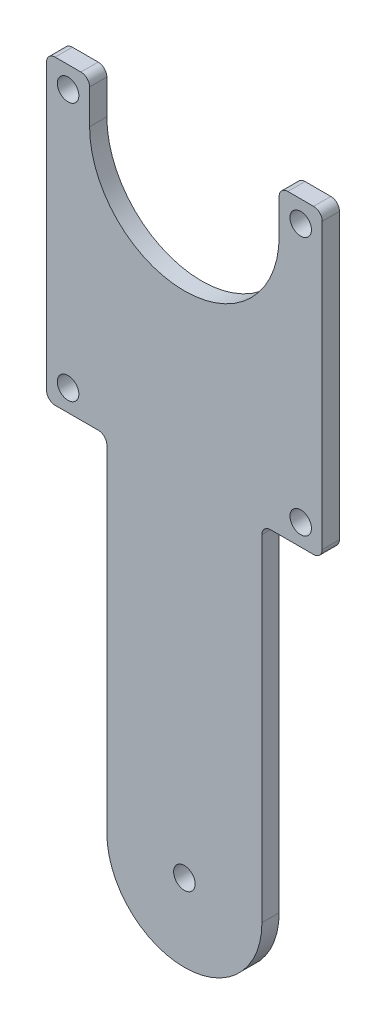
SolidWorks part; units mm, degrees
material "自訂玻璃纖維"
ref_plane "前基準面" through (0, 0, 0) normal (0, 0, 1) x (1, 0, 0)
ref_plane "上基準面" through (0, 0, 0) normal (0, 1, 0) x (1, 0, 0)
ref_plane "右基準面" through (0, 0, 0) normal (1, 0, 0) x (0, 0, -1)
sketch "草圖1" plane through (0, 0, 0) normal (0, 0, 1) x (1, 0, 0)
  line L0 (-6.9514, 19.5958) -> (-3.9514, 19.5958)
  line L1 (-7.9514, 18.5958) -> (-7.9514, -10.4042)
  line L2 (24.0486, -10.4042) -> (24.0486, 18.5958)
  line L3 (24.0486, -10.4042) -> (24.0486, -14.4042)
  line L4 (20.0486, 19.5958) -> (23.0486, 19.5958)
  line L5 (19.0486, 15.5958) -> (19.0486, 14.5958)
  line L6 (-2.9514, 18.5958) -> (-2.9514, 15.5958)
  line L7 (23.0486, -15.4042) -> (18.0486, -15.4042)
  line L8 (19.0486, 18.5958) -> (19.0486, 15.5958)
  line L9 (17.0486, -16.4042) -> (17.0486, -55.4042)
  line L10 (-7.9514, -10.4042) -> (-7.9514, -14.4042)
  line L11 (-6.9514, -15.4042) -> (-1.9514, -15.4042)
  line L12 (-0.9514, -16.4042) -> (-0.9514, -55.4042)
  line L13 (-2.9514, 14.5958) -> (-2.9514, 15.5958)
  circle A0 centre (-5.4514, -12.9042) radius 1.25
  circle A1 centre (21.5486, -12.9042) radius 1.25
  circle A2 centre (-5.4514, 17.0958) radius 1.25
  circle A3 centre (21.5486, 17.0958) radius 1.25
  arc A4 (19.0486, 14.5958) -> (-2.9514, 14.5958) centre (8.0486, 14.5958) cw
  arc A5 (23.0486, 19.5958) -> (24.0486, 18.5958) centre (23.0486, 18.5958) cw
  arc A6 (20.0486, 19.5958) -> (19.0486, 18.5958) centre (20.0486, 18.5958) ccw
  arc A7 (-0.9514, -55.4042) -> (17.0486, -55.4042) centre (8.0486, -55.4042) ccw
  arc A8 (-3.9514, 19.5958) -> (-2.9514, 18.5958) centre (-3.9514, 18.5958) cw
  arc A9 (-6.9514, 19.5958) -> (-7.9514, 18.5958) centre (-6.9514, 18.5958) ccw
  arc A10 (-7.9514, -14.4042) -> (-6.9514, -15.4042) centre (-6.9514, -14.4042) ccw
  circle A11 centre (8.0486, -55.4042) radius 1.25
  arc A12 (-1.9514, -15.4042) -> (-0.9514, -16.4042) centre (-1.9514, -16.4042) cw
  arc A13 (18.0486, -15.4042) -> (17.0486, -16.4042) centre (18.0486, -16.4042) ccw
  arc A14 (24.0486, -14.4042) -> (23.0486, -15.4042) centre (23.0486, -14.4042) cw
  point P20 (24.0486, 19.5958)
  point P25 (-2.9514, 14.5958)
  point P28 (-2.9514, 19.5958)
  point P31 (8.0486, -55.4042)
  point P47 (-1.2443, -15.6971)
  dimension "D3" = 2.5
  dimension "D4" = 27
  dimension "D5" = 27
  dimension "D7" = 39
  dimension "D10" = 2.5
  dimension "D13" = 9
  dimension "D11" = 2.5
  dimension "D16" = 1
  dimension "D1" = 2.5
  dimension "D2" = 5
  dimension "D6" = 30
  dimension "D8" = 2.5
  dimension "D9" = 2.5
  dimension "D12" = 2.5
  dimension "D14" = 2.5
extrude "填料-伸長1" add sketch "草圖1" along normal blind 2
